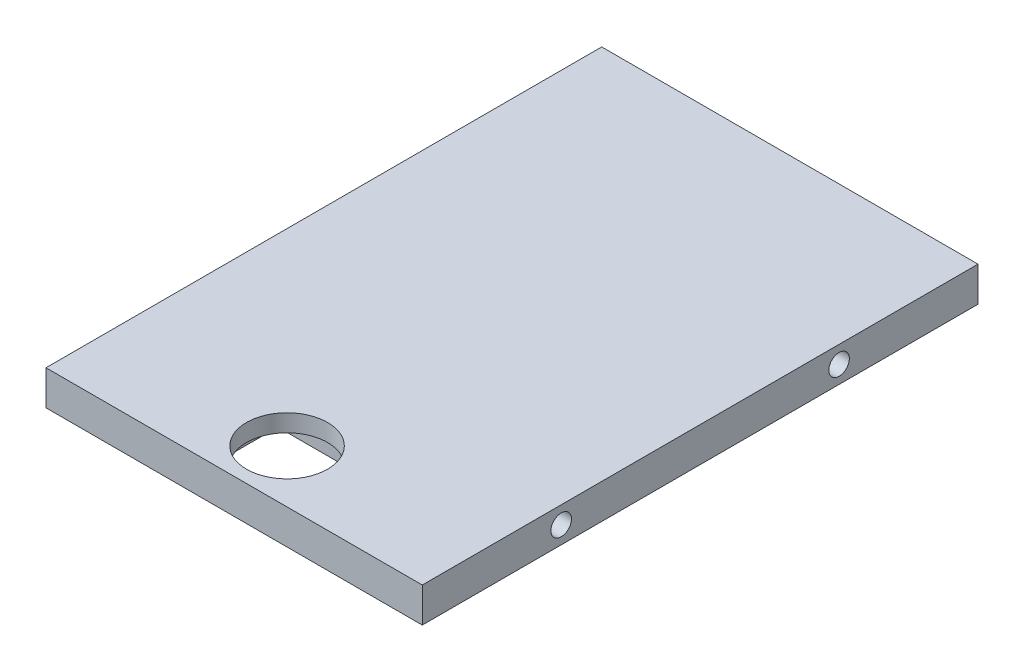
SolidWorks part; units mm, degrees
ref_plane "Front Plane" through (0, 0, 0) normal (0, 0, 1) x (1, 0, 0)
ref_plane "Top Plane" through (0, 0, 0) normal (0, 1, 0) x (1, 0, 0)
ref_plane "Right Plane" through (0, 0, 0) normal (1, 0, 0) x (0, 0, -1)
sketch "Sketch1" plane through (0, 0, 0) normal (0, 1, 0) x (1, 0, 0)
  line L1 (0, 0) -> (32.5, 0)
  line L2 (0, 0) -> (0, 48)
  line L3 (0, 48) -> (32.5, 48)
  line L4 (32.5, 0) -> (32.5, 48)
extrude "Boss-Extrude1" add sketch "Sketch1" along normal blind 3
sketch "Sketch2" plane through (0, 3, 0) normal (0, 1, 0) x (1, 0, 0)
  line L0 (0, 0) -> (0, 3)
  line L1 (0, 48) -> (0, 0) construction
  line L2 (0, 3) -> (32.5, 3)
  line L3 (32.5, 0) -> (32.5, 48) construction
  line L4 (0, 1.5) -> (32.5, 1.5)
  line L5 (16.25, 3) -> (0, 0)
  line L6 (16.25, 3) -> (32.5, 0)
  line L7 (0, 48) -> (0, 45)
  line L8 (0, 45) -> (32.5, 45)
  line L9 (0, 46.5) -> (32.5, 46.5)
  line L10 (0, 48) -> (16.25, 45)
  line L11 (16.25, 45) -> (32.5, 48)
sketch "Sketch3" plane through (0, 3, 0) normal (0, 1, 0) x (1, 0, 0)
  line L0 (0, 48) -> (16.25, 45) construction
  line L1 (16.25, 45) -> (32.5, 48) construction
  line L2 (16.25, 3) -> (0, 0) construction
  line L3 (16.25, 3) -> (32.5, 0) construction
  circle A0 centre (8.125, 46.5) radius 1.22
  circle A1 centre (24.375, 46.5) radius 1.22
  circle A2 centre (8.125, 1.5) radius 1.22
  circle A3 centre (24.375, 1.5) radius 1.22
sketch "Sketch4" plane through (0, 0, 0) normal (-1, 0, 0) x (0, 0, 1)
  line L0 (-48, 3) -> (-24, 0)
  line L1 (-48, 0) -> (0, 0) construction
  line L2 (-24, 0) -> (0, 3)
  line L3 (0, 3) -> (0, 0)
  line L4 (0, 0) -> (-24, 3)
  line L5 (-48, 3) -> (0, 3) construction
  line L6 (-24, 3) -> (-48, 0)
hole_wizard "#2-56 Tapped Hole1" positions "Sketch5" profile "Sketch6" tap size "#2-56" standard "ANSI Inch"
sketch "Sketch5" plane through (0, 0, 0) normal (-1, 0, 0) x (0, 0, 1)
  line L0 (-48, 3) -> (-24, 0) construction
  line L1 (-24, 0) -> (0, 3) construction
  point P0 (-36, 1.5)
  point P4 (-12, 1.5)
sketch "Sketch6" plane through (0, 1.5, -36) normal (0, 1, 0) x (0, 0, 1)
  line L0 (0, 0) -> (0, 8)
  line L1 (0, 8) -> (0.889, 7.4658)
  line L2 (0.889, 7.4658) -> (0.889, 0)
  line L5 (0.889, 0) -> (0, 0)
  line L10 (0, 8) -> (-0.889, 7.4658) construction
  line L11 (0, -6.35) -> (0, 107.95) construction
  dimension "Tap Drill Dia." = 1.778
  dimension "Tap Drill Depth" = 8
  dimension "Drill Angle" = 118
cosmetic thread "Hole Thread1" parameters "D1"=4.37, "D2"=2.1844
cosmetic thread "Hole Thread2" parameters "D1"=4.37, "D2"=2.1844
sketch "Sketch7" plane through (32.5, 0, 0) normal (1, 0, 0) x (0, 0, -1)
  line L0 (0, 3) -> (24, 0)
  line L1 (0, 0) -> (48, 0) construction
  line L2 (24, 0) -> (48, 3)
  line L3 (48, 3) -> (48, 0)
  line L4 (48, 0) -> (24, 3)
  line L5 (0, 3) -> (48, 3) construction
  line L6 (24, 3) -> (0, 0)
hole_wizard "#2-56 Tapped Hole2" positions "Sketch8" profile "Sketch9" tap size "#2-56" standard "ANSI Inch"
sketch "Sketch8" plane through (32.5, 0, 0) normal (1, 0, 0) x (0, 0, -1)
  line L0 (0, 3) -> (24, 0) construction
  line L1 (24, 0) -> (48, 3) construction
  point P0 (12, 1.5)
  point P4 (36, 1.5)
sketch "Sketch9" plane through (32.5, 1.5, -12) normal (0, 1, 0) x (0, 0, -1)
  line L0 (0, 0) -> (0, 8)
  line L1 (0, 8) -> (0.889, 7.4658)
  line L2 (0.889, 7.4658) -> (0.889, 0)
  line L5 (0.889, 0) -> (0, 0)
  line L10 (0, 8) -> (-0.889, 7.4658) construction
  line L11 (0, -6.35) -> (0, 107.95) construction
  dimension "Tap Drill Dia." = 1.778
  dimension "Tap Drill Depth" = 8
  dimension "Drill Angle" = 118
cosmetic thread "Hole Thread3" parameters "D1"=4.37, "D2"=2.1844
cosmetic thread "Hole Thread4" parameters "D1"=4.37, "D2"=2.1844
sketch "Sketch10" plane through (0, 3, 0) normal (0, 1, 0) x (1, 0, 0)
  line L0 (0, 0) -> (0, 4.57)
  line L1 (0, 48) -> (0, 0) construction
  line L2 (0, 4.57) -> (32.5, 4.57)
  line L3 (32.5, 0) -> (32.5, 48) construction
  circle A0 centre (16.25, 4.57) radius 3.5
sketch "Sketch11" plane through (0, 0, 0) normal (0, -1, 0) x (-1, 0, 0)
  line L1 (0, 4.57) -> (-32.5, 4.57) construction
  line L2 (-21.05, 4.57) -> (-21.05, 8.57)
  line L3 (-21.05, 8.57) -> (-11.45, 8.57)
  line L4 (-11.45, 8.57) -> (-11.45, 0.57)
  line L5 (-11.45, 0.57) -> (-21.05, 0.57)
  line L6 (-21.05, 0.57) -> (-21.05, 4.57)
extrude "Cut-Extrude2" cut sketch "Sketch11" against normal blind 1.5
extrude "Cut-Extrude3" cut sketch "Sketch10" against normal blind 3 contours A0
